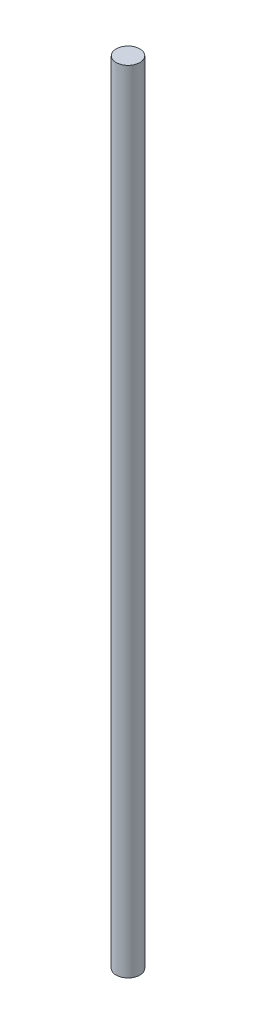
SolidWorks part; units mm, degrees
ref_plane "Front" through (0, 0, 0) normal (0, 0, 1) x (1, 0, 0)
ref_plane "Top" through (0, 0, 0) normal (0, 1, 0) x (1, 0, 0)
ref_plane "Right" through (0, 0, 0) normal (1, 0, 0) x (0, 0, -1)
sketch "Sketch1" plane through (0, 0, 0) normal (0, 1, 0) x (1, 0, 0)
  circle A0 centre (0, 0) radius 1.5
extrude "Boss-Extrude1" add sketch "Sketch1" along normal blind 100
